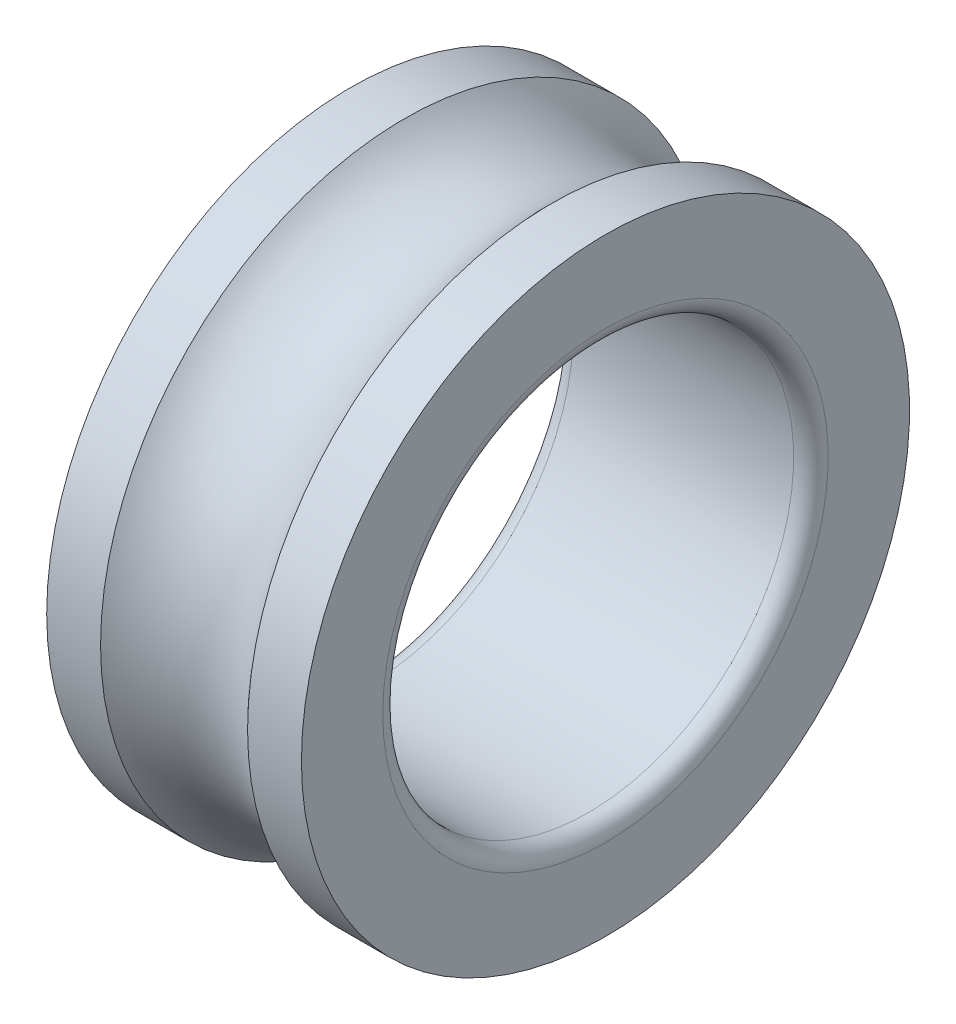
SolidWorks part; units mm, degrees
ref_plane "Plan de face" through (0, 0, 0) normal (0, 0, 1) x (1, 0, 0)
ref_plane "Plan de dessus" through (0, 0, 0) normal (0, 1, 0) x (1, 0, 0)
ref_plane "Plan de droite" through (0, 0, 0) normal (1, 0, 0) x (0, 0, -1)
sketch "Esquisse1" plane through (0, 0, 0) normal (0, 0, 1) x (1, 0, 0)
  line L0 (-31.0724, 0) -> (31.0724, 0) construction
  line L1 (0, 0) -> (0, 25) construction
  line L2 (-13.4, 25) -> (13.4, 25)
  line L3 (-15.5, 27.1) -> (-15.5, 37)
  line L4 (-15.5, 37) -> (-8.9443, 37)
  line L5 (15.5, 27.1) -> (15.5, 37)
  line L6 (-15.5, 25) -> (15.5, 37) construction
  line L7 (-15.5, 37) -> (15.5, 25) construction
  line L8 (8.9443, 37) -> (15.5, 37)
  arc A0 (-8.9443, 37) -> (8.9443, 37) centre (0, 45) ccw
  arc A1 (13.4, 25) -> (15.5, 27.1) centre (13.4, 27.1) ccw
  arc A2 (-13.4, 25) -> (-15.5, 27.1) centre (-13.4, 27.1) cw
  point P0 (0, 31)
  point P4 (0, 0)
  dimension "D5" = 12
  dimension "D6" = 2.1
  dimension "D1" = 31
  dimension "D2" = 25
  dimension "D3" = 37
  dimension "D4" = 8
revolve "Révolution1" add sketch "Esquisse1" angle 360 about L0
